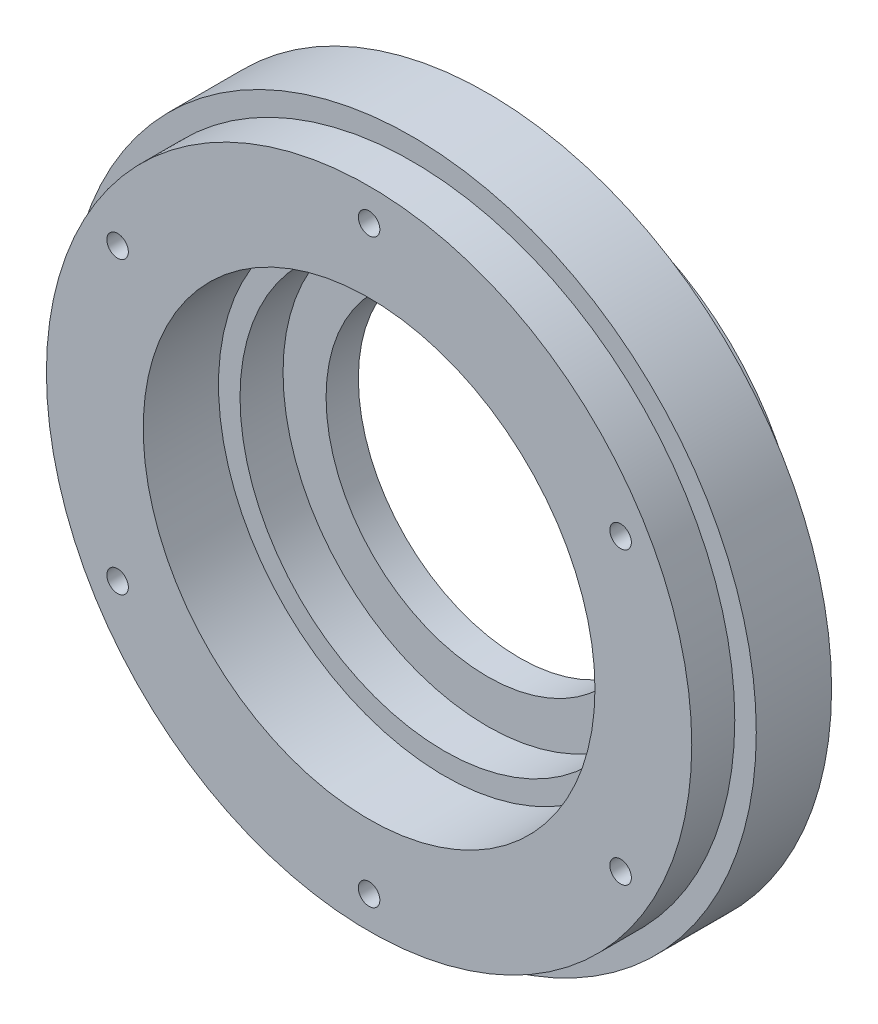
SolidWorks part; units mm, degrees
ref_plane "前视基准面" through (0, 0, 0) normal (0, 0, 1) x (1, 0, 0)
ref_plane "上视基准面" through (0, 0, 0) normal (0, 1, 0) x (1, 0, 0)
ref_plane "右视基准面" through (0, 0, 0) normal (1, 0, 0) x (0, 0, -1)
sketch "草图1" plane through (0, 0, 0) normal (0, 0, 1) x (1, 0, 0)
  circle A0 centre (0, 0) radius 19
  circle A1 centre (0, 0) radius 32
  dimension "D1" = 38
  dimension "D2" = 64
extrude "凸台-拉伸1" add sketch "草图1" along normal blind 4
sketch "草图2" plane through (0, 0, 4) normal (0, 0, 1) x (1, 0, 0)
  circle A0 centre (0, 0) radius 21
  circle A1 centre (0, 0) radius 32
  dimension "D1" = 42
  dimension "D2" = 64
extrude "凸台-拉伸2" add sketch "草图2" along normal blind 7
sketch "草图3" plane through (0, 0, 11) normal (0, 0, 1) x (1, 0, 0)
  circle A0 centre (0, 27) radius 1
  circle A1 centre (23.3827, 13.5) radius 1
  circle A2 centre (23.3827, -13.5) radius 1
  circle A3 centre (0, -27) radius 1
  circle A4 centre (-23.3827, -13.5) radius 1
  circle A5 centre (-23.3827, 13.5) radius 1
  point P12 (0, 0)
  dimension "D1" = 2
  dimension "D2" = 27
  dimension "D3" = 6
extrude "切除-拉伸1" cut sketch "草图3" against normal through all
sketch "草图4" plane through (0, 0, 0) normal (0, 0, -1) x (-1, 0, 0)
  line L0 (21.0733, 13.5) -> (22.228, 11.5)
  line L1 (-1.1547, 25) -> (1.1547, 25)
  line L2 (1.1547, 25) -> (2.3094, 27)
  line L3 (2.3094, 27) -> (1.1547, 29)
  line L4 (1.1547, 29) -> (-1.1547, 29)
  line L5 (-1.1547, 29) -> (-2.3094, 27)
  line L6 (-2.3094, 27) -> (-1.1547, 25)
  line L7 (22.228, 11.5) -> (24.5374, 11.5)
  line L8 (24.5374, 11.5) -> (25.6921, 13.5)
  line L9 (25.6921, 13.5) -> (24.5374, 15.5)
  line L10 (24.5374, 15.5) -> (22.228, 15.5)
  line L11 (22.228, 15.5) -> (21.0733, 13.5)
  line L12 (22.228, -11.5) -> (21.0733, -13.5)
  line L13 (21.0733, -13.5) -> (22.228, -15.5)
  line L14 (22.228, -15.5) -> (24.5374, -15.5)
  line L15 (24.5374, -15.5) -> (25.6921, -13.5)
  line L16 (25.6921, -13.5) -> (24.5374, -11.5)
  line L17 (24.5374, -11.5) -> (22.228, -11.5)
  line L18 (1.1547, -25) -> (-1.1547, -25)
  line L19 (-1.1547, -25) -> (-2.3094, -27)
  line L20 (-2.3094, -27) -> (-1.1547, -29)
  line L21 (-1.1547, -29) -> (1.1547, -29)
  line L22 (1.1547, -29) -> (2.3094, -27)
  line L23 (2.3094, -27) -> (1.1547, -25)
  line L24 (-21.0733, -13.5) -> (-22.228, -11.5)
  line L25 (-22.228, -11.5) -> (-24.5374, -11.5)
  line L26 (-24.5374, -11.5) -> (-25.6921, -13.5)
  line L27 (-25.6921, -13.5) -> (-24.5374, -15.5)
  line L28 (-24.5374, -15.5) -> (-22.228, -15.5)
  line L29 (-22.228, -15.5) -> (-21.0733, -13.5)
  line L30 (-22.228, 11.5) -> (-21.0733, 13.5)
  line L31 (-21.0733, 13.5) -> (-22.228, 15.5)
  line L32 (-22.228, 15.5) -> (-24.5374, 15.5)
  line L33 (-24.5374, 15.5) -> (-25.6921, 13.5)
  line L34 (-25.6921, 13.5) -> (-24.5374, 11.5)
  line L35 (-24.5374, 11.5) -> (-22.228, 11.5)
  circle A0 centre (0, 27) radius 2 construction
  point P41 (0, 0)
  dimension "D1" = 4
  dimension "D2" = 6
extrude "切除-拉伸2" cut sketch "草图4" against normal blind 6
sketch "草图5" plane through (0, 0, 0) normal (0, 0, -1) x (-1, 0, 0)
  circle A0 centre (0, 0) radius 15
  circle A1 centre (0, 0) radius 22.45
  dimension "D1" = 30
  dimension "D2" = 44.9
extrude "凸台-拉伸3" add sketch "草图5" along normal blind 7
sketch "草图6" plane through (0, 0, -7) normal (0, 0, -1) x (-1, 0, 0)
  circle A0 centre (0, 0) radius 21.05
  dimension "D1" = 42.1
extrude "切除-拉伸3" cut sketch "草图6" against normal blind 4
sketch "草图7" plane through (0, 0, 11) normal (0, 0, 1) x (1, 0, 0)
  circle A0 centre (0, 0) radius 30
  circle A1 centre (0, 0) radius 32 construction
  circle A2 centre (0, 0) radius 32
  dimension "D1" = 60
extrude "切除-拉伸4" cut sketch "草图7" against normal blind 4
